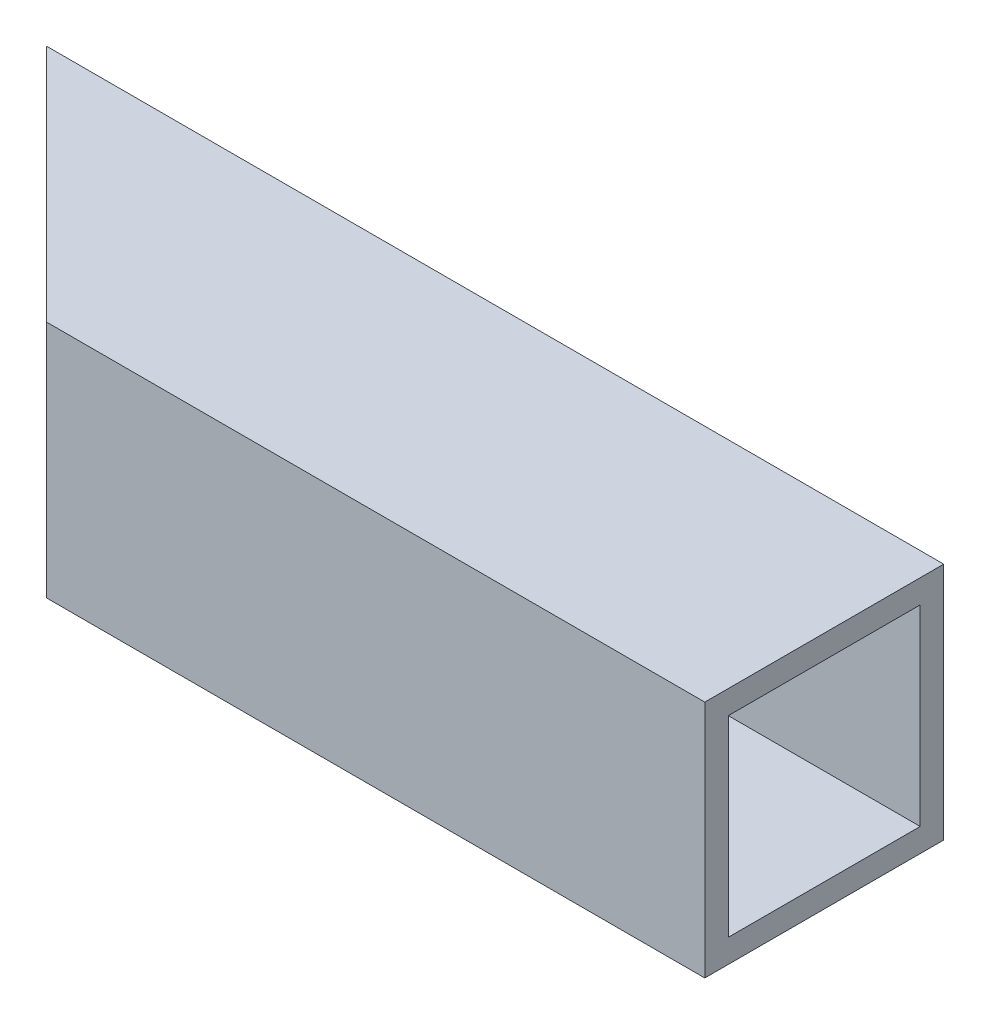
SolidWorks part; units mm, degrees
ref_plane "Front Plane" through (0, 0, 0) normal (0, 0, 1) x (1, 0, 0)
ref_plane "Top Plane" through (0, 0, 0) normal (0, 1, 0) x (1, 0, 0)
ref_plane "Right Plane" through (0, 0, 0) normal (1, 0, 0) x (0, 0, -1)
sketch "Sketch2" plane through (0, 0, 0) normal (1, 0, 0) x (0, 0, -1)
  line L1 (-12.7, 12.7) -> (12.7, 12.7)
  line L2 (-12.7, 12.7) -> (-12.7, -12.7)
  line L3 (-12.7, -12.7) -> (12.7, -12.7)
  line L4 (12.7, 12.7) -> (12.7, -12.7)
  line L5 (-12.7, 12.7) -> (12.7, -12.7) construction
  line L6 (-12.7, -12.7) -> (12.7, 12.7) construction
  line L7 (-10.2, 10.2) -> (10.2, 10.2)
  line L8 (-10.2, 10.2) -> (-10.2, -10.2)
  line L9 (-10.2, -10.2) -> (10.2, -10.2)
  line L10 (10.2, 10.2) -> (10.2, -10.2)
  line L11 (-10.2, 10.2) -> (10.2, -10.2) construction
  line L12 (-10.2, -10.2) -> (10.2, 10.2) construction
  point P0 (0, 0)
  point P6 (0, 0)
  dimension "D1" = 25.4
  dimension "D2" = 25.4
  dimension "D3" = 20.4
extrude "Boss-Extrude1" add sketch "Sketch2" along normal blind 95.4
sketch "Sketch3" plane through (0, 12.7, 0) normal (0, 1, 0) x (1, 0, 0)
  line L1 (95.4, -12.7) -> (0, -12.7) construction
  line L4 (0, -12.7) -> (0, 12.7)
  line L5 (0, 12.7) -> (25.4, -12.7)
  line L6 (25.4, -12.7) -> (0, -12.7)
  dimension "D2" = 45
extrude "Cut-Extrude1" cut sketch "Sketch3" against normal through all
